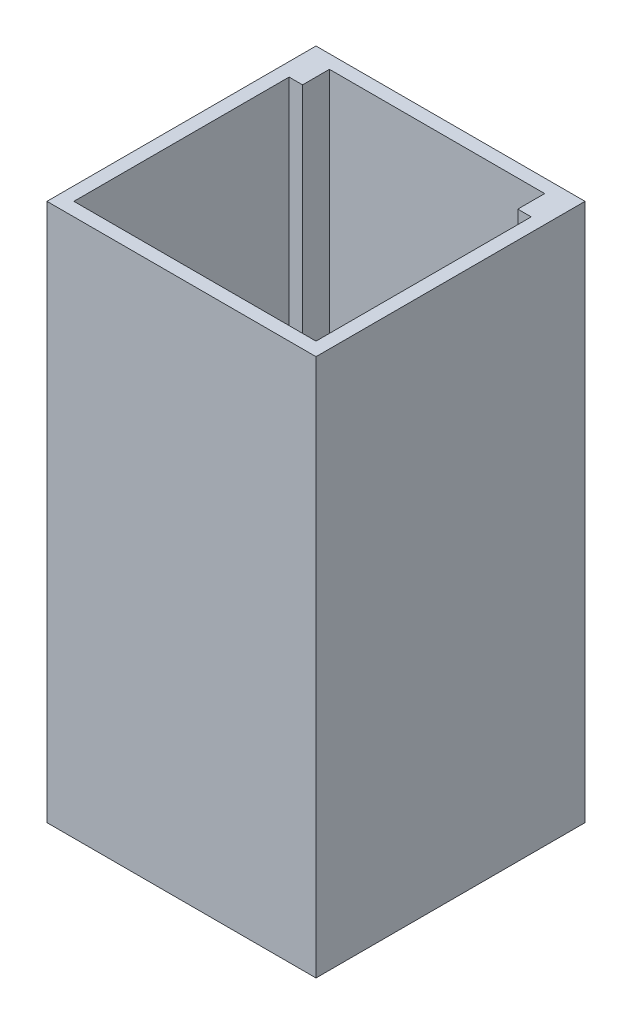
SolidWorks part; units mm, degrees
ref_plane "Front Plane" through (0, 0, 0) normal (1, 0, 0) x (0, 1, 0)
ref_plane "Top Plane" through (0, 0, 0) normal (0, 0, 1) x (0, 1, 0)
ref_plane "Right Plane" through (0, 0, 0) normal (0, 1, 0) x (-1, 0, 0)
sketch "Sketch1" plane through (0, 0, 0) normal (0, 1, 0) x (-1, 0, 0)
  line L1 (-50, 50) -> (50, 50)
  line L2 (-50, 50) -> (-50, -50)
  line L3 (-50, -50) -> (50, -50)
  line L4 (50, 50) -> (50, -50)
  line L5 (-50, 50) -> (50, -50) construction
  line L6 (-50, -50) -> (50, 50) construction
  point P0 (0, 0)
  dimension "D1" = 100
  dimension "D2" = 100
extrude "Boss-Extrude1" add sketch "Sketch1" along normal mid plane 200
shell "Shell1" thickness 5
sketch "Sketch2" plane through (0, 100, 0) normal (0, 1, 0) x (-1, 0, 0)
  line L0 (0, 16.6384) -> (0, -52.852) construction
  line L1 (-45, -45) -> (-40, -45)
  line L2 (-45, -45) -> (-45, -35)
  line L3 (-45, -35) -> (-40, -35)
  line L4 (-40, -45) -> (-40, -35)
  line L5 (45, -35) -> (40, -35)
  line L6 (40, -45) -> (40, -35)
  line L7 (45, -45) -> (40, -45)
  line L8 (45, -45) -> (45, -35)
  dimension "D1" = 5
extrude "Boss-Extrude2" add sketch "Sketch2" against normal up to next
